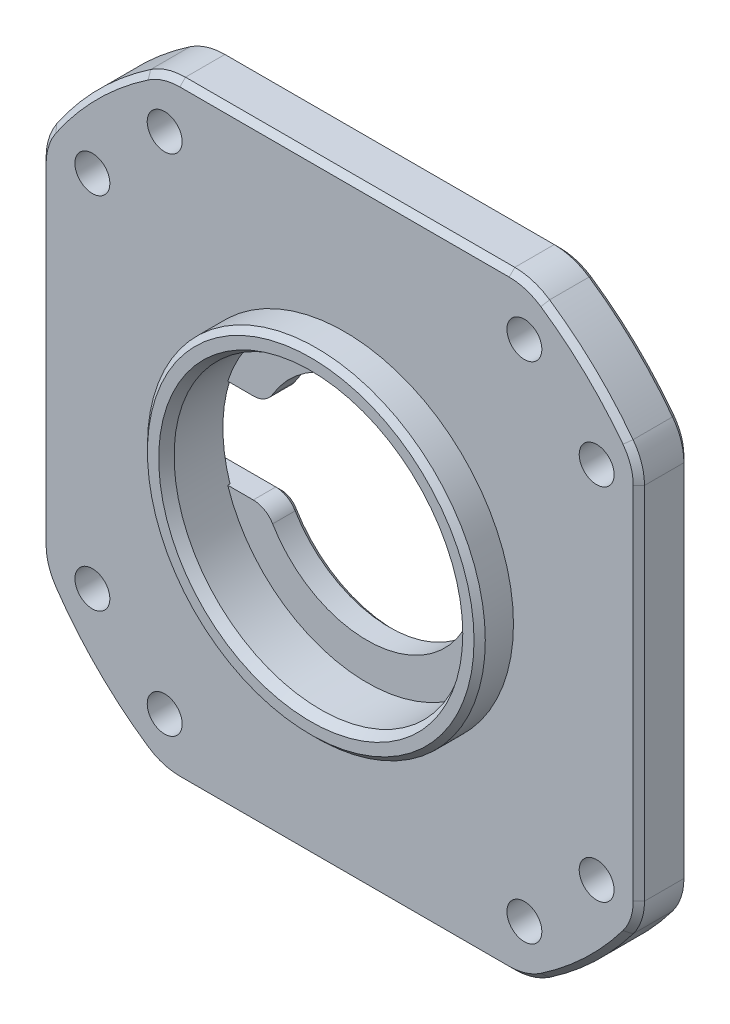
SolidWorks part; units mm, degrees
material "6061 合金"
ref_plane "前视基准面" through (0, 0, 0) normal (0, 0, 1) x (1, 0, 0)
ref_plane "上视基准面" through (0, 0, 0) normal (0, 1, 0) x (1, 0, 0)
ref_plane "右视基准面" through (0, 0, 0) normal (1, 0, 0) x (0, 0, -1)
sketch "草图2" plane through (0, 0, 0) normal (0, 0, 1) x (1, 0, 0)
  line L0 (0, 0) -> (0, 42.4253) construction
  line L1 (0, 0) -> (-58.848, 0) construction
  line L2 (0, 0) -> (-24.9229, 34.9407) construction
  line L3 (0, 0) -> (-44.1643, 31.5021) construction
  line L5 (-25.5, 25.5) -> (25.5, 25.5)
  line L6 (-25.5, 25.5) -> (-25.5, -25.5)
  line L7 (-25.5, -25.5) -> (25.5, -25.5)
  line L8 (25.5, 25.5) -> (25.5, -25.5)
  line L9 (-25.5, 25.5) -> (25.5, -25.5) construction
  line L10 (-25.5, -25.5) -> (25.5, 25.5) construction
  circle A0 centre (0, 0) radius 27.5 construction
  circle A1 centre (-22.3882, 15.9693) radius 1.55
  circle A2 centre (-15.9693, 22.3882) radius 1.55
  circle A3 centre (15.9693, 22.3882) radius 1.55
  circle A4 centre (22.3882, 15.9693) radius 1.55
  circle A5 centre (22.3882, -15.9693) radius 1.55
  circle A6 centre (15.9693, -22.3882) radius 1.55
  circle A7 centre (-15.9693, -22.3882) radius 1.55
  circle A8 centre (-22.3882, -15.9693) radius 1.55
  dimension "D1" = 55
  dimension "D4" = 3.1
  dimension "D2" = 35.5
  dimension "D3" = 35.5
  dimension "D5" = 51
  dimension "D6" = 51
extrude "凸台-拉伸1" add sketch "草图2" along normal blind 4.5
sketch "草图4" plane through (0, 0, 4.5) normal (0, 0, 1) x (1, 0, 0)
  line L0 (-25.5, -15.8035) -> (-25.5, -25.5)
  line L1 (15.8035, -25.5) -> (25.5, -25.5)
  line L2 (25.5, 15.8035) -> (25.5, 25.5)
  line L3 (-15.8035, 25.5) -> (-25.5, 25.5)
  line L4 (25.5, -25.5) -> (25.5, 25.5)
  line L5 (25.5, 25.5) -> (-25.5, 25.5)
  line L6 (-25.5, 25.5) -> (-25.5, -25.5)
  line L7 (-25.5, -25.5) -> (25.5, -25.5)
  line L8 (25.5, -25.5) -> (25.5, -15.8035)
  line L9 (25.5, 25.5) -> (15.8035, 25.5)
  line L10 (-25.5, 25.5) -> (-25.5, 15.8035)
  line L11 (-25.5, -25.5) -> (-15.8035, -25.5)
  arc A0 (-25.5, -15.8035) -> (-15.8035, -25.5) centre (0, 0) ccw
  arc A1 (15.8035, -25.5) -> (25.5, -15.8035) centre (0, 0) ccw
  arc A2 (25.5, 15.8035) -> (15.8035, 25.5) centre (0, 0) ccw
  arc A3 (-15.8035, 25.5) -> (-25.5, 15.8035) centre (0, 0) ccw
  dimension "D1" = 60
  dimension "D2" = 0
extrude "切除-拉伸1" cut sketch "草图4" against normal blind 5
fillet "圆角1" radius 4 8 edges at (-15.8035, 25.5, 2.25) (15.8035, 25.5, 2.25) (25.5, 15.8035, 2.25) (25.5, -15.8035, 2.25) (15.8035, -25.5, 2.25) (-15.8035, -25.5, 2.25) (-25.5, -15.8035, 2.25) (-25.5, 15.8035, 2.25)
sketch "草图5" plane through (0, 0, 4.5) normal (0, 0, 1) x (1, 0, 0)
  circle A0 centre (0, 0) radius 13
  dimension "D1" = 26
extrude "切除-拉伸2" cut sketch "草图5" against normal blind 2
sketch "草图6" plane through (0, 0, 2.5) normal (0, 0, 1) x (1, 0, 0)
  circle A0 centre (0, 0) radius 9.75
  dimension "D1" = 19.5
extrude "切除-拉伸3" cut sketch "草图6" against normal through all both and the other way through all
sketch "草图8" plane through (0, 0, 0) normal (0, 0, -1) x (-1, 0, 0)
  line L0 (0, 0) -> (30.2395, 0) construction
  line L2 (8.8917, 4) -> (36.8917, 4)
  line L3 (8.8917, 4) -> (8.8917, -4)
  line L4 (8.8917, -4) -> (36.8917, -4)
  line L5 (36.8917, 4) -> (36.8917, -4)
  line L6 (8.8917, 4) -> (36.8917, -4) construction
  line L7 (8.8917, -4) -> (36.8917, 4) construction
  circle A0 centre (0, 0) radius 9.75 construction
  point P3 (22.8917, 0)
  dimension "D1" = 8
  dimension "D2" = 28
extrude "切除-拉伸4" cut sketch "草图8" against normal blind 2.3 and the other way through all
sketch "草图9" plane through (0, 0, 0) normal (0, 0, -1) x (-1, 0, 0)
  line L0 (-26.1363, 17.5791) -> (-26.1363, -17.5791)
  line L1 (25.5, 5) -> (25.5, -4)
  line L8 (25.5, -14.6202) -> (25.5, -4)
  line L10 (25.5, -4) -> (8.8917, -4)
  line L13 (-14.6202, -27) -> (14.6202, -27)
  line L14 (27, -14.6202) -> (27, 14.6202)
  line L15 (14.6202, 27) -> (-14.6202, 27)
  line L19 (25.5, 5) -> (25.5, 14.6202)
  line L20 (25.5, -14.6202) -> (25.5, -4)
  line L28 (8.8917, 4) -> (25.5, 4)
  line L30 (25.5, 4) -> (25.5, 14.6202)
  line L34 (14.6202, 25.5) -> (-14.6202, 25.5)
  line L36 (14.6202, 25.5) -> (-14.6202, 25.5)
  line L38 (-25.5, 14.6202) -> (-25.5, -14.6202)
  line L39 (-25.5, 14.6202) -> (-25.5, -14.6202)
  line L40 (-14.6202, -25.5) -> (14.6202, -25.5)
  line L41 (-14.6202, -25.5) -> (14.6202, -25.5)
  arc A15 (25.5, 14.6202) -> (24.8077, 16.8695) centre (21.5, 14.6202) ccw
  arc A16 (25.5, 14.6202) -> (24.8077, 16.8695) centre (21.5, 14.6202) ccw
  arc A20 (8.8917, 4) -> (8.8917, -4) centre (0, 0) ccw
  arc A21 (24.8077, 16.8695) -> (16.8695, 24.8077) centre (0, 0) ccw
  arc A22 (24.8077, 16.8695) -> (16.8695, 24.8077) centre (0, 0) ccw
  arc A23 (16.8695, 24.8077) -> (14.6202, 25.5) centre (14.6202, 21.5) ccw
  arc A24 (16.8695, 24.8077) -> (14.6202, 25.5) centre (14.6202, 21.5) ccw
  arc A25 (-14.6202, 25.5) -> (-16.8695, 24.8077) centre (-14.6202, 21.5) ccw
  arc A26 (-14.6202, 25.5) -> (-16.8695, 24.8077) centre (-14.6202, 21.5) ccw
  arc A27 (-16.8695, 24.8077) -> (-24.8077, 16.8695) centre (0, 0) ccw
  arc A29 (-26.1363, -17.5791) -> (-26.0481, -17.7129) centre (-21.5, -14.6202) ccw
  arc A30 (-26.0481, -17.7129) -> (-17.7129, -26.0481) centre (0, 0) ccw
  arc A31 (-17.7129, -26.0481) -> (-14.6202, -27) centre (-14.6202, -21.5) ccw
  arc A32 (14.6202, -27) -> (17.7129, -26.0481) centre (14.6202, -21.5) ccw
  arc A33 (17.7129, -26.0481) -> (26.0481, -17.7129) centre (0, 0) ccw
  arc A34 (26.0481, -17.7129) -> (27, -14.6202) centre (21.5, -14.6202) ccw
  arc A35 (27, 14.6202) -> (26.0481, 17.7129) centre (21.5, 14.6202) ccw
  arc A36 (26.0481, 17.7129) -> (17.7129, 26.0481) centre (0, 0) ccw
  arc A37 (17.7129, 26.0481) -> (14.6202, 27) centre (14.6202, 21.5) ccw
  arc A38 (-14.6202, 27) -> (-17.7129, 26.0481) centre (-14.6202, 21.5) ccw
  arc A39 (-17.7129, 26.0481) -> (-26.0481, 17.7129) centre (0, 0) ccw
  arc A40 (-26.0481, 17.7129) -> (-26.1363, 17.5791) centre (-21.5, 14.6202) ccw
  arc A42 (-16.8695, 24.8077) -> (-24.8077, 16.8695) centre (0, 0) ccw
  arc A43 (-24.8077, 16.8695) -> (-25.5, 14.6202) centre (-21.5, 14.6202) ccw
  arc A44 (-24.8077, 16.8695) -> (-25.5, 14.6202) centre (-21.5, 14.6202) ccw
  arc A45 (-25.5, -14.6202) -> (-24.8077, -16.8695) centre (-21.5, -14.6202) ccw
  arc A46 (-25.5, -14.6202) -> (-24.8077, -16.8695) centre (-21.5, -14.6202) ccw
  arc A47 (-24.8077, -16.8695) -> (-16.8695, -24.8077) centre (0, 0) ccw
  arc A65 (-24.8077, -16.8695) -> (-16.8695, -24.8077) centre (0, 0) ccw
  arc A66 (-16.8695, -24.8077) -> (-14.6202, -25.5) centre (-14.6202, -21.5) ccw
  arc A67 (-16.8695, -24.8077) -> (-14.6202, -25.5) centre (-14.6202, -21.5) ccw
  arc A68 (14.6202, -25.5) -> (16.8695, -24.8077) centre (14.6202, -21.5) ccw
  arc A69 (14.6202, -25.5) -> (16.8695, -24.8077) centre (14.6202, -21.5) ccw
  arc A70 (16.8695, -24.8077) -> (24.8077, -16.8695) centre (0, 0) ccw
  arc A71 (16.8695, -24.8077) -> (24.8077, -16.8695) centre (0, 0) ccw
  arc A72 (24.8077, -16.8695) -> (25.5, -14.6202) centre (21.5, -14.6202) ccw
  arc A73 (24.8077, -16.8695) -> (25.5, -14.6202) centre (21.5, -14.6202) ccw
  line M29 (25.5, -14.6202) -> (25.5, -4)
  line M37 (25.5, 4) -> (25.5, 14.6202)
  arc M38 (25.5, 14.6202) -> (24.8077, 16.8695) centre (21.5, 14.6202) ccw
  arc M39 (24.8077, 16.8695) -> (16.8695, 24.8077) centre (0, 0) ccw
  arc M40 (16.8695, 24.8077) -> (14.6202, 25.5) centre (14.6202, 21.5) ccw
  line M41 (14.6202, 25.5) -> (-14.6202, 25.5)
  arc M42 (-14.6202, 25.5) -> (-16.8695, 24.8077) centre (-14.6202, 21.5) ccw
  arc M43 (-16.8695, 24.8077) -> (-24.8077, 16.8695) centre (0, 0) ccw
  arc M44 (-24.8077, 16.8695) -> (-25.5, 14.6202) centre (-21.5, 14.6202) ccw
  line M45 (-25.5, 14.6202) -> (-25.5, -14.6202)
  arc M46 (-25.5, -14.6202) -> (-24.8077, -16.8695) centre (-21.5, -14.6202) ccw
  arc M47 (-24.8077, -16.8695) -> (-16.8695, -24.8077) centre (0, 0) ccw
  arc M48 (-16.8695, -24.8077) -> (-14.6202, -25.5) centre (-14.6202, -21.5) ccw
  line M49 (-14.6202, -25.5) -> (14.6202, -25.5)
  arc M50 (14.6202, -25.5) -> (16.8695, -24.8077) centre (14.6202, -21.5) ccw
  arc M51 (16.8695, -24.8077) -> (24.8077, -16.8695) centre (0, 0) ccw
  arc M52 (24.8077, -16.8695) -> (25.5, -14.6202) centre (21.5, -14.6202) ccw
  dimension "D1" = 0
extrude "凸台-拉伸2" add sketch "草图9" against normal up to surface (4.5 mm away) contours A39 A40 L0 A29 A30 A31 L13 A32 A33 A34 L14 A35 A36 A37 L15 A38 L1 M37 M29 M52 M51 M50 M49 M48 M47 M46 M45 M44 M43 M42 M41 M40 M39 M38
sketch "草图11" plane through (0, 0, 0) normal (0, 0, -1) x (-1, 0, 0)
  line L0 (25.5, 4) -> (25.5, -4)
  line L1 (25.5, -4) -> (27, -4)
  line L3 (27, -4) -> (27, 4)
  line L4 (27, 4) -> (25.5, 4)
  line L5 (27, -14.6202) -> (27, 14.6202) construction
extrude "切除-拉伸7" cut sketch "草图11" against normal up to surface (2.3 mm away) and the other way through all up to face at (-17.4104, 0, 2.3)
fillet "圆角3" radius 1 3 edges at (-27, -4, 1.15) (-27, 0, 2.3) (-27, 4, 1.15)
fillet "圆角4" radius 5 2 edges at (26.1363, 17.5791, 2.25) (26.1363, -17.5791, 2.25)
sketch "草图12" plane through (0, 0, 4.5) normal (0, 0, 1) x (1, 0, 0)
  circle A0 centre (0, 0) radius 13
  circle A1 centre (0, 0) radius 15
  dimension "D1" = 26
  dimension "D2" = 30
extrude "凸台-拉伸3" add sketch "草图12" along normal blind 3
sketch "草图13" plane through (0, 0, 2.3) normal (0, 0, -1) x (-1, 0, 0)
  line L0 (8.8917, 4) -> (12.3693, 4)
  line L1 (26, 4) -> (8.8917, 4) construction
  line L2 (8.8917, -4) -> (12.3693, -4)
  line L3 (8.8917, -4) -> (26, -4) construction
  arc A0 (8.8917, -4) -> (8.8917, 4) centre (0, 0) ccw construction
  arc A1 (8.8917, -4) -> (8.8917, 4) centre (0, 0) ccw
  circle A2 centre (0, 0) radius 13 construction
  arc A3 (12.3693, -4) -> (12.3693, 4) centre (0, 0) ccw
extrude "切除-拉伸8" cut sketch "草图13" against normal up to surface (0.2 mm away) up to face at (9.75, 0, 2.5)
fillet "圆角5" radius 2 2 edges at (-8.8917, -4, 1.25) (-8.8917, 4, 1.25)
fillet "圆角6" [suppressed] radius 2
chamfer "倒角1" distance 0.5 angle 45 41 edges at (15, 0, 7.5) (-18.0513, -4, 0) (-26.7071, -4.2929, 0) (-27, -9.8101, 0) (-26.7566, -16.2381, 0) (-18.0513, 4, 0) (-22.2739, -22.2739, 0) (-26.7071, 4.2929, 0) (-16.2381, -26.7566, 0) (-27, 9.8101, 0) (0, -27, 0) (-26.7566, 16.2381, 0) (16.2381, -26.7566, 0) (-22.2739, 22.2739, 0) (21.7065, -22.8271, 0) (-16.2381, 26.7566, 0) (25.8765, -17.5752, 4.5) (25.8765, -17.5752, 0) (0, 27, 0) (26.1363, 0, 0) (16.2381, 26.7566, 0) (25.8765, 17.5752, 4.5) (25.8765, 17.5752, 0) (21.7065, 22.8271, 0) (-22.2739, -22.2739, 4.5) (-26.7566, -16.2381, 4.5) (-16.2381, -26.7566, 4.5) (-27, 0, 4.5) (0, -27, 4.5) (-26.7566, 16.2381, 4.5) (16.2381, -26.7566, 4.5) (-22.2739, 22.2739, 4.5) (21.7065, -22.8271, 4.5) (-16.2381, 26.7566, 4.5) (0, 27, 4.5) (26.1363, 0, 4.5) (16.2381, 26.7566, 4.5) (21.7065, 22.8271, 4.5) (-9.1133, -4.2618, 0) (9.75, 0, 0) (-9.1133, 4.2618, 0)
chamfer "倒角2" distance 0.5 angle 60 1 edges at (13, 0, 7.5)
